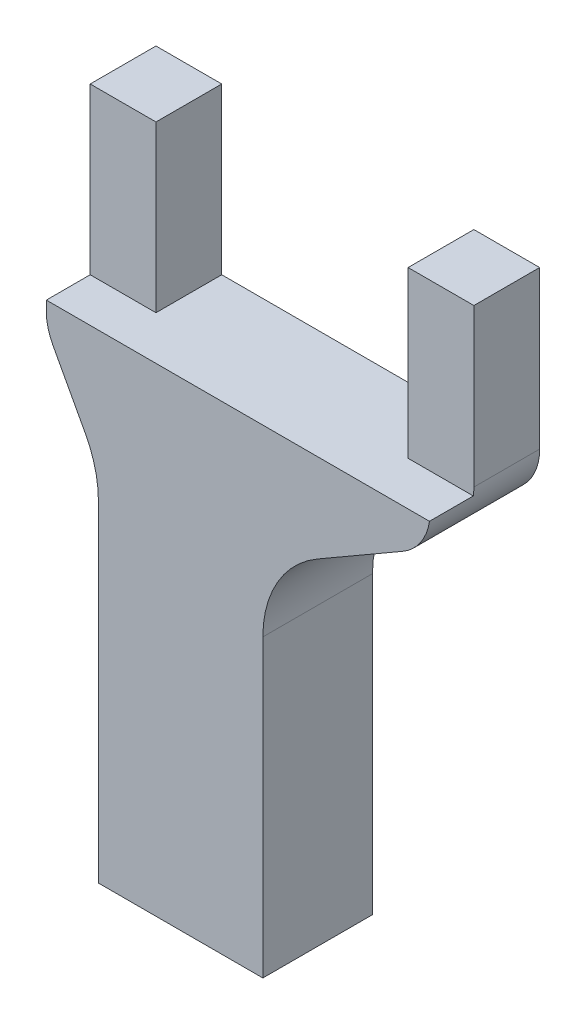
SolidWorks part; units mm, degrees
ref_plane "Front Plane" through (0, 0, 0) normal (0, 0, 1) x (1, 0, 0)
ref_plane "Top Plane" through (0, 0, 0) normal (0, 1, 0) x (1, 0, 0)
ref_plane "Right Plane" through (0, 0, 0) normal (1, 0, 0) x (0, 0, -1)
sketch "Sketch1" plane through (0, 0, 0) normal (0, 0, 1) x (1, 0, 0)
  line L2 (-7.5, 467.3207) -> (-7.5, 500.038)
  line L3 (-6.25, 511.0002) -> (16.75, 511.0002)
  line L4 (7.5, 467.3207) -> (7.5, 500.038)
  line L7 (7.5, 467.3207) -> (-7.5, 467.3207)
  line L9 (-6.25, 526.0712) -> (-6.25, 511.0002)
  line L11 (16.75, 526.0712) -> (16.75, 511.0002)
  line L15 (22.75, 526.0712) -> (22.75, 508.8426)
  line L16 (22.75, 508.8426) -> (7.5, 500.038)
  line L17 (16.75, 526.0712) -> (22.75, 526.0712)
  line L18 (-6.25, 526.0712) -> (-12.25, 526.0712)
  line L19 (-12.25, 526.0712) -> (-12.25, 508.8426)
  line L20 (-12.25, 508.8426) -> (-7.5, 500.038)
  dimension "D5" = 6
  dimension "D6" = 6
extrude "Boss-Extrude1" add sketch "Sketch1" along normal blind 10
fillet "Fillet1" radius 10 2 edges at (-7.5, 500.038, 5) (7.5, 500.038, 5)
fillet "Fillet2" radius 5 2 edges at (-12.25, 508.8426, 5) (22.75, 508.8426, 5)
sketch "Sketch2" plane through (0, 0, 10) normal (0, 0, 1) x (1, 0, 0)
  line L0 (16.75, 511.0002) -> (-6.25, 511.0002) construction
  line L1 (-12.25, 526.0712) -> (22.75, 526.0712)
  line L2 (-12.25, 526.0712) -> (-12.25, 511.0002)
  line L3 (-12.25, 511.0002) -> (22.75, 511.0002)
  line L4 (22.75, 526.0712) -> (22.75, 511.0002)
  line L5 (22.75, 511.7293) -> (22.75, 526.0712) construction
  dimension "D1" = 0
  dimension "D2" = 0
extrude "Cut-Extrude1" cut sketch "Sketch2" against normal blind 4
